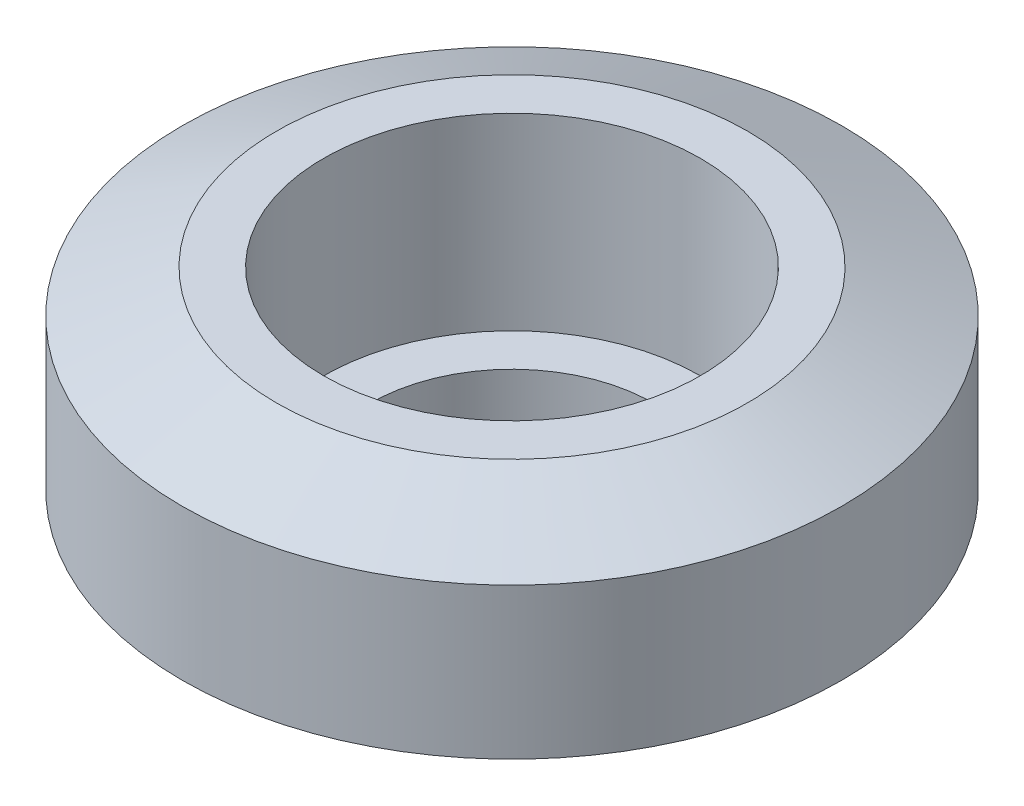
SolidWorks part; units mm, degrees
ref_plane "前视基准面" through (0, 0, 0) normal (0, 0, 1) x (1, 0, 0)
ref_plane "上视基准面" through (0, 0, 0) normal (0, 1, 0) x (1, 0, 0)
ref_plane "右视基准面" through (0, 0, 0) normal (1, 0, 0) x (0, 0, -1)
other "Configuration Table"
sketch "草图1" plane through (0, 0, 0) normal (0, 0, 1) x (1, 0, 0)
  line L0 (-27.6446, 0) -> (36.9, 0) construction
  line L1 (0, 5) -> (10, 5)
  line L2 (10, 5) -> (14, 3.2)
  line L3 (14, 3.2) -> (14, -3.2)
  line L4 (14, -3.2) -> (10, -5)
  line L5 (10, -5) -> (0, -5)
  line L6 (0, -5) -> (0, 5)
  line L7 (12, 4.1) -> (12, -4.1) construction
  dimension "D1" = 8.2
  dimension "D2" = 2
  dimension "D3" = 14
  dimension "D4" = 10
revolve "旋转1" add sketch "草图1" angle 360 about L6
sketch "草图2" plane through (0, 0, 0) normal (0, 1, 0) x (1, 0, 0)
  circle A0 centre (0, 0) radius 8
  dimension "D1" = 16
extrude "切除-拉伸1" cut sketch "草图2" against normal blind 8 from surface at 5 starting at face at (0, 5, -10)
sketch "草图3" plane through (0, 0, 0) normal (0, 1, 0) x (1, 0, 0)
  circle A0 centre (0, 0) radius 6
  dimension "D1" = 12
extrude "切除-拉伸2" cut sketch "草图3" against normal through all both and the other way through all
